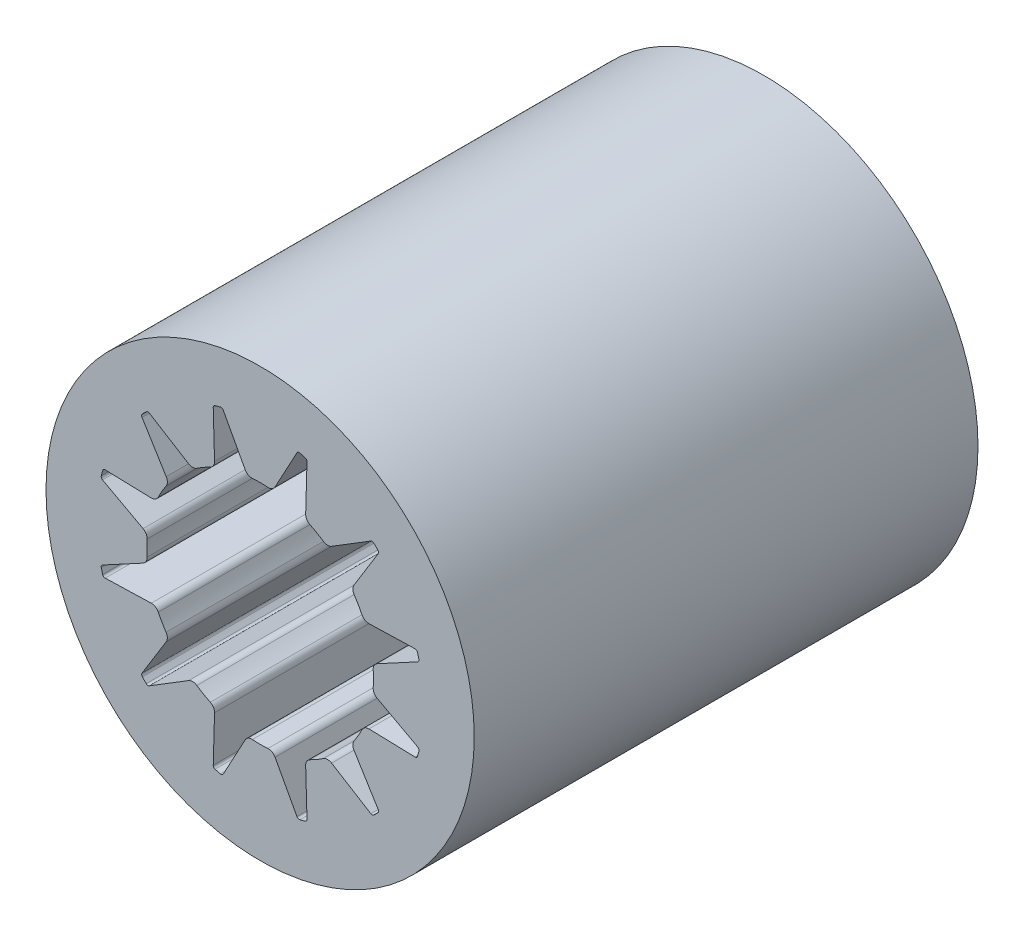
SolidWorks part; units mm, degrees
ref_plane "Front Plane" through (0, 0, 0) normal (0, 0, 1) x (1, 0, 0)
ref_plane "Top Plane" through (0, 0, 0) normal (0, 1, 0) x (1, 0, 0)
ref_plane "Right Plane" through (0, 0, 0) normal (1, 0, 0) x (0, 0, -1)
sketch "Sketch1" plane through (0, 0, 0) normal (0, 0, 1) x (1, 0, 0)
  line L0 (0, 6.5) -> (0, 4.5) construction
  line L1 (-1.4633, 6.2566) -> (-0.5939, 4.6461)
  line L2 (1.4633, 6.2566) -> (0.5939, 4.6461)
  line L3 (4.3956, 4.6867) -> (2.8374, 3.7267)
  line L4 (1.861, 6.1501) -> (1.8087, 4.3206)
  line L5 (6.1501, 1.861) -> (4.3206, 1.8087)
  line L6 (4.6867, 4.3956) -> (3.7267, 2.8374)
  line L7 (6.2566, -1.4633) -> (4.6461, -0.5939)
  line L8 (6.2566, 1.4633) -> (4.6461, 0.5939)
  line L9 (4.6867, -4.3956) -> (3.7267, -2.8374)
  line L10 (6.1501, -1.861) -> (4.3206, -1.8087)
  line L11 (1.861, -6.1501) -> (1.8087, -4.3206)
  line L12 (4.3956, -4.6867) -> (2.8374, -3.7267)
  line L13 (-1.4633, -6.2566) -> (-0.5939, -4.6461)
  line L14 (1.4633, -6.2566) -> (0.5939, -4.6461)
  line L15 (-4.3956, -4.6867) -> (-2.8374, -3.7267)
  line L16 (-1.861, -6.1501) -> (-1.8087, -4.3206)
  line L17 (-6.1501, -1.861) -> (-4.3206, -1.8087)
  line L18 (-4.6867, -4.3956) -> (-3.7267, -2.8374)
  line L19 (-6.2566, 1.4633) -> (-4.6461, 0.5939)
  line L20 (-6.2566, -1.4633) -> (-4.6461, -0.5939)
  line L21 (-4.6867, 4.3956) -> (-3.7267, 2.8374)
  line L22 (-6.1501, 1.861) -> (-4.3206, 1.8087)
  line L23 (-1.861, 6.1501) -> (-1.8087, 4.3206)
  line L24 (-4.3956, 4.6867) -> (-2.8374, 3.7267)
  arc A0 (-3.7332, 2.5126) -> (-4.0426, 1.9768) centre (0, 0) ccw
  circle A1 centre (0, 0) radius 8.5
  arc A2 (-6.2491, 1.7886) -> (-6.3062, 1.5756) centre (0, 0) ccw
  circle A3 centre (0, 0) radius 4.5 construction
  arc A4 (-4.4894, 0.3093) -> (-4.4894, -0.3093) centre (0, 0) ccw
  arc A5 (-4.0426, -1.9768) -> (-3.7332, -2.5126) centre (0, 0) ccw
  arc A6 (-0.3093, -4.4894) -> (0.3093, -4.4894) centre (0, 0) ccw
  arc A7 (1.9768, -4.0426) -> (2.5126, -3.7332) centre (0, 0) ccw
  arc A8 (3.7332, -2.5126) -> (4.0426, -1.9768) centre (0, 0) ccw
  arc A9 (4.4894, -0.3093) -> (4.4894, 0.3093) centre (0, 0) ccw
  arc A10 (4.0426, 1.9768) -> (3.7332, 2.5126) centre (0, 0) ccw
  arc A11 (2.5126, 3.7332) -> (1.9768, 4.0426) centre (0, 0) ccw
  arc A12 (-1.9768, 4.0426) -> (-2.5126, 3.7332) centre (0, 0) ccw
  arc A13 (0.3093, 4.4894) -> (-0.3093, 4.4894) centre (0, 0) ccw
  circle A14 centre (0, 0) radius 6.5 construction
  arc A15 (-6.3062, -1.5756) -> (-6.2491, -1.7886) centre (0, 0) ccw
  arc A16 (-4.6735, -4.5176) -> (-4.5176, -4.6735) centre (0, 0) ccw
  arc A17 (-1.7886, -6.2491) -> (-1.5756, -6.3062) centre (0, 0) ccw
  arc A18 (-2.5126, -3.7332) -> (-1.9768, -4.0426) centre (0, 0) ccw
  arc A19 (1.5756, -6.3062) -> (1.7886, -6.2491) centre (0, 0) ccw
  arc A20 (4.5176, -4.6735) -> (4.6735, -4.5176) centre (0, 0) ccw
  arc A21 (6.2491, -1.7886) -> (6.3062, -1.5756) centre (0, 0) ccw
  arc A22 (6.3062, 1.5756) -> (6.2491, 1.7886) centre (0, 0) ccw
  arc A23 (4.6735, 4.5176) -> (4.5176, 4.6735) centre (0, 0) ccw
  arc A24 (1.7886, 6.2491) -> (1.5756, 6.3062) centre (0, 0) ccw
  arc A25 (-1.5756, 6.3062) -> (-1.7886, 6.2491) centre (0, 0) ccw
  arc A26 (-4.5176, 4.6735) -> (-4.6735, 4.5176) centre (0, 0) ccw
  arc A27 (-2.8374, 3.7267) -> (-2.5126, 3.7332) centre (-2.6801, 3.9821) ccw
  arc A28 (-1.8087, 4.3206) -> (-1.9768, 4.0426) centre (-2.1086, 4.3121) cw
  arc A29 (-0.5939, 4.6461) -> (-0.3093, 4.4894) centre (-0.3299, 4.7886) ccw
  arc A30 (0.5939, 4.6461) -> (0.3093, 4.4894) centre (0.3299, 4.7886) cw
  arc A31 (1.8087, 4.3206) -> (1.9768, 4.0426) centre (2.1086, 4.3121) ccw
  arc A32 (2.8374, 3.7267) -> (2.5126, 3.7332) centre (2.6801, 3.9821) cw
  arc A33 (4.3206, 1.8087) -> (4.0426, 1.9768) centre (4.3121, 2.1086) cw
  arc A34 (3.7267, 2.8374) -> (3.7332, 2.5126) centre (3.9821, 2.6801) ccw
  arc A35 (4.6461, 0.5939) -> (4.4894, 0.3093) centre (4.7886, 0.3299) ccw
  arc A36 (4.6461, -0.5939) -> (4.4894, -0.3093) centre (4.7886, -0.3299) cw
  arc A37 (4.3206, -1.8087) -> (4.0426, -1.9768) centre (4.3121, -2.1086) ccw
  arc A38 (3.7267, -2.8374) -> (3.7332, -2.5126) centre (3.9821, -2.6801) cw
  arc A39 (2.8374, -3.7267) -> (2.5126, -3.7332) centre (2.6801, -3.9821) ccw
  arc A40 (1.8087, -4.3206) -> (1.9768, -4.0426) centre (2.1086, -4.3121) cw
  arc A41 (0.5939, -4.6461) -> (0.3093, -4.4894) centre (0.3299, -4.7886) ccw
  arc A42 (-0.5939, -4.6461) -> (-0.3093, -4.4894) centre (-0.3299, -4.7886) cw
  arc A43 (-2.8374, -3.7267) -> (-2.5126, -3.7332) centre (-2.6801, -3.9821) cw
  arc A44 (-1.8087, -4.3206) -> (-1.9768, -4.0426) centre (-2.1086, -4.3121) ccw
  arc A45 (-3.7267, -2.8374) -> (-3.7332, -2.5126) centre (-3.9821, -2.6801) ccw
  arc A46 (-4.3206, -1.8087) -> (-4.0426, -1.9768) centre (-4.3121, -2.1086) cw
  arc A47 (-4.6461, -0.5939) -> (-4.4894, -0.3093) centre (-4.7886, -0.3299) ccw
  arc A48 (-4.6461, 0.5939) -> (-4.4894, 0.3093) centre (-4.7886, 0.3299) cw
  arc A49 (-3.7267, 2.8374) -> (-3.7332, 2.5126) centre (-3.9821, 2.6801) cw
  arc A50 (-4.3206, 1.8087) -> (-4.0426, 1.9768) centre (-4.3121, 2.1086) ccw
  arc A51 (-6.1501, 1.861) -> (-6.2491, 1.7886) centre (-6.1529, 1.7611) ccw
  arc A52 (-6.2566, 1.4633) -> (-6.3062, 1.5756) centre (-6.2091, 1.5513) cw
  arc A53 (-6.1501, -1.861) -> (-6.2491, -1.7886) centre (-6.1529, -1.7611) cw
  arc A54 (-6.2566, -1.4633) -> (-6.3062, -1.5756) centre (-6.2091, -1.5513) ccw
  arc A55 (-4.6867, -4.3956) -> (-4.6735, -4.5176) centre (-4.6016, -4.4481) ccw
  arc A56 (-4.3956, -4.6867) -> (-4.5176, -4.6735) centre (-4.4481, -4.6016) cw
  arc A57 (-1.861, -6.1501) -> (-1.7886, -6.2491) centre (-1.7611, -6.1529) ccw
  arc A58 (-1.4633, -6.2566) -> (-1.5756, -6.3062) centre (-1.5513, -6.2091) cw
  arc A59 (1.4633, -6.2566) -> (1.5756, -6.3062) centre (1.5513, -6.2091) ccw
  arc A60 (1.861, -6.1501) -> (1.7886, -6.2491) centre (1.7611, -6.1529) cw
  arc A61 (4.3956, -4.6867) -> (4.5176, -4.6735) centre (4.4481, -4.6016) ccw
  arc A62 (4.6867, -4.3956) -> (4.6735, -4.5176) centre (4.6016, -4.4481) cw
  arc A63 (6.1501, -1.861) -> (6.2491, -1.7886) centre (6.1529, -1.7611) ccw
  arc A64 (6.2566, -1.4633) -> (6.3062, -1.5756) centre (6.2091, -1.5513) cw
  arc A65 (6.2566, 1.4633) -> (6.3062, 1.5756) centre (6.2091, 1.5513) ccw
  arc A66 (6.1501, 1.861) -> (6.2491, 1.7886) centre (6.1529, 1.7611) cw
  arc A67 (4.6867, 4.3956) -> (4.6735, 4.5176) centre (4.6016, 4.4481) ccw
  arc A68 (4.3956, 4.6867) -> (4.5176, 4.6735) centre (4.4481, 4.6016) cw
  arc A69 (1.861, 6.1501) -> (1.7886, 6.2491) centre (1.7611, 6.1529) ccw
  arc A70 (1.4633, 6.2566) -> (1.5756, 6.3062) centre (1.5513, 6.2091) cw
  arc A71 (-1.4633, 6.2566) -> (-1.5756, 6.3062) centre (-1.5513, 6.2091) ccw
  arc A72 (-1.861, 6.1501) -> (-1.7886, 6.2491) centre (-1.7611, 6.1529) cw
  arc A73 (-4.6867, 4.3956) -> (-4.6735, 4.5176) centre (-4.6016, 4.4481) cw
  arc A74 (-4.3956, 4.6867) -> (-4.5176, 4.6735) centre (-4.4481, 4.6016) ccw
  point P59 (0, 0)
  point P64 (-0.5, 4.4721)
  point P67 (0.5, 4.4721)
  point P148 (1.5, 6.3246)
  point P151 (-1.5, 6.3246)
  dimension "D1" = 4
  dimension "D4" = 9
  dimension "D7" = 0.3
  dimension "D8" = 0.3
  dimension "D9" = 0.3
  dimension "D10" = 0.3
  dimension "D11" = 0.3
  dimension "D12" = 0.3
  dimension "D13" = 0.3
  dimension "D14" = 0.3
  dimension "D15" = 0.3
  dimension "D16" = 0.3
  dimension "D17" = 0.3
  dimension "D18" = 0.3
  dimension "D19" = 0.3
  dimension "D20" = 0.3
  dimension "D21" = 0.3
  dimension "D22" = 0.3
  dimension "D23" = 0.3
  dimension "D24" = 0.3
  dimension "D25" = 0.3
  dimension "D26" = 0.3
  dimension "D27" = 0.3
  dimension "D28" = 0.3
  dimension "D29" = 0.3
  dimension "D30" = 0.3
  dimension "D31" = 0.1
  dimension "D32" = 0.1
  dimension "D33" = 0.1
  dimension "D34" = 0.1
  dimension "D35" = 0.1
  dimension "D36" = 0.1
  dimension "D37" = 0.1
  dimension "D38" = 0.1
  dimension "D39" = 0.1
  dimension "D40" = 0.1
  dimension "D41" = 0.1
  dimension "D42" = 0.1
  dimension "D43" = 0.1
  dimension "D44" = 0.1
  dimension "D45" = 0.1
  dimension "D46" = 0.1
  dimension "D47" = 0.1
  dimension "D48" = 0.1
  dimension "D49" = 0.1
  dimension "D50" = 0.1
  dimension "D51" = 0.1
  dimension "D52" = 0.1
  dimension "D53" = 0.1
  dimension "D54" = 0.1
  dimension "D3" = 1.5
  dimension "D5" = 0.5
  dimension "D2" = 2
  dimension "D6" = 12
extrude "Boss-Extrude1" add sketch "Sketch1" along normal blind 20
